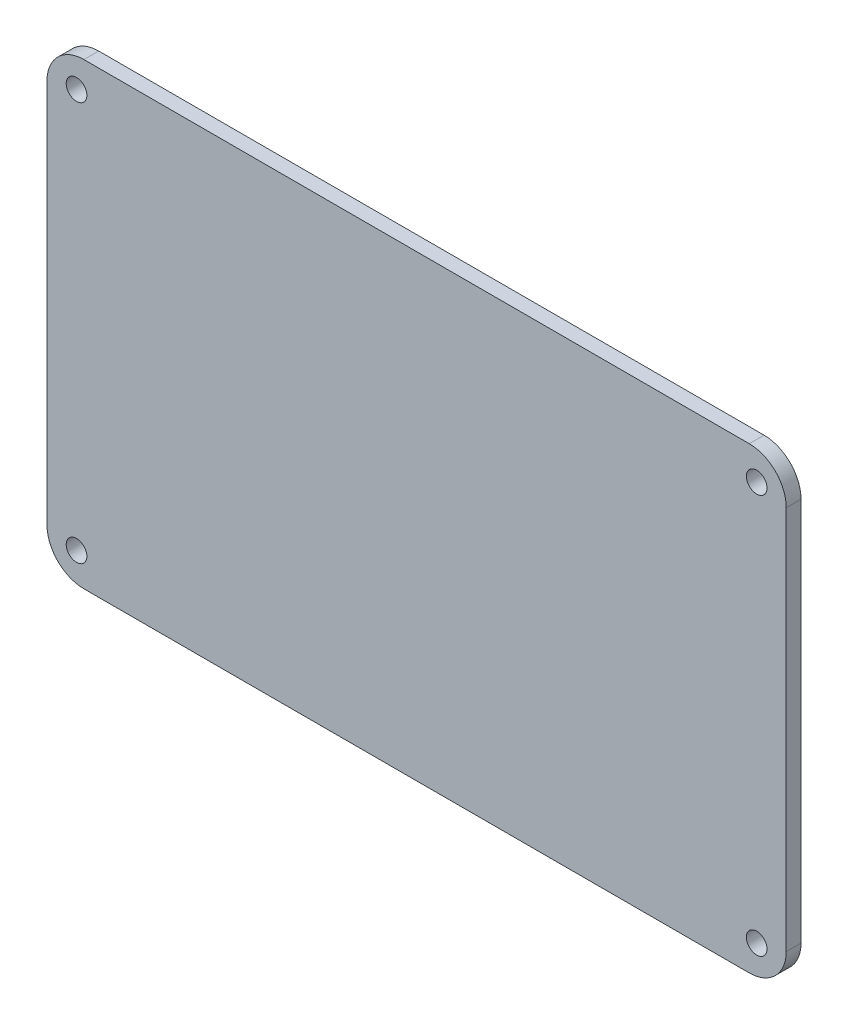
SolidWorks part; units mm, degrees
ref_plane "前视基准面" through (0, 0, 0) normal (0, 0, 1) x (1, 0, 0)
ref_plane "上视基准面" through (0, 0, 0) normal (0, 1, 0) x (1, 0, 0)
ref_plane "右视基准面" through (0, 0, 0) normal (1, 0, 0) x (0, 0, -1)
other "Configuration Table"
sketch "草图1" plane through (0, 0, 0) normal (0, 0, 1) x (1, 0, 0)
  line L0 (50, 62) -> (50, 0) construction
  line L1 (0, 0) -> (100, 0)
  line L2 (0, 0) -> (0, 62)
  line L3 (0, 62) -> (100, 62)
  line L4 (100, 0) -> (100, 62)
  line L5 (0, 31) -> (100, 31) construction
  circle A0 centre (4, 58) radius 1.4
  circle A1 centre (4, 4) radius 1.4
  circle A2 centre (96, 4) radius 1.4
  circle A3 centre (96, 58) radius 1.4
  dimension "D5" = 2.8
  dimension "D1" = 100
  dimension "D2" = 62
  dimension "D3" = 4
  dimension "D4" = 4
extrude "凸台-拉伸1" add sketch "草图1" along normal blind 2
fillet "圆角1" radius 5 4 edges at (0, 0, 1) (100, 0, 1) (100, 62, 1) (0, 62, 1)
